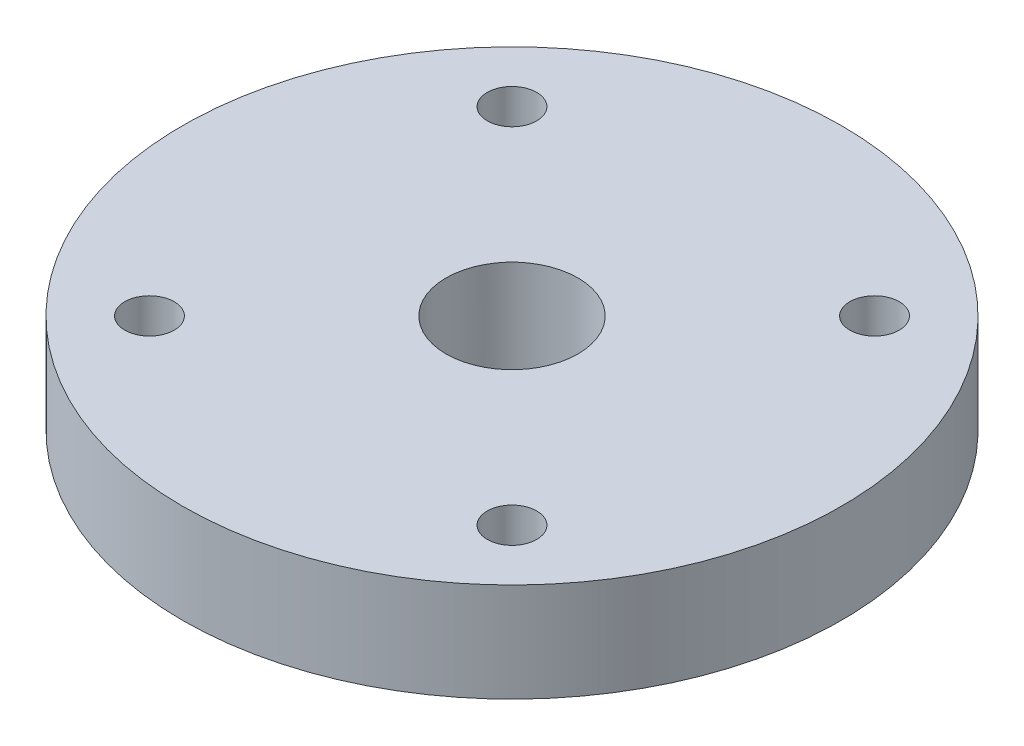
SolidWorks part; units mm, degrees
material "Acrylic (Medium-high impact)"
ref_plane "Front Plane" through (0, 0, 0) normal (0, 0, 1) x (1, 0, 0)
ref_plane "Top Plane" through (0, 0, 0) normal (0, 1, 0) x (1, 0, 0)
ref_plane "Right Plane" through (0, 0, 0) normal (1, 0, 0) x (0, 0, -1)
sketch "Sketch1" plane through (0, 0, 0) normal (0, 1, 0) x (1, 0, 0)
  circle A0 centre (0, 0) radius 20
  dimension "D1" = 40
extrude "Arm Distans Boss-Extrude1" add sketch "Sketch1" along normal blind 6
sketch "Sketch2" plane through (0, 6, 0) normal (0, 1, 0) x (1, 0, 0)
  line L0 (-11, 11) -> (0, 0) construction
  line L1 (11, 11) -> (-11, 11) construction
  line L2 (11, 11) -> (11, -11) construction
  line L3 (11, -11) -> (-11, -11) construction
  line L4 (-11, 11) -> (-11, -11) construction
  line L5 (0, 0) -> (-11, -11) construction
  line L6 (0, 0) -> (11, -11) construction
  line L7 (0, 0) -> (11, 11) construction
  circle A0 centre (11, 11) radius 1.5
  circle A1 centre (-11, 11) radius 1.5
  circle A2 centre (-11, -11) radius 1.5
  circle A3 centre (11, -11) radius 1.5
  dimension "D2" = 3
  dimension "D1" = 22
extrude "Mounting Holes Cut-Extrude1" cut sketch "Sketch2" against normal up to surface (6 mm away) up to face at (0, 0, 20)
sketch "Sketch3" plane through (0, 0, 0) normal (0, -1, 0) x (1, 0, 0)
  circle A0 centre (0, 0) radius 4
  dimension "D1" = 8
extrude "Cut-Extrude1" cut sketch "Sketch3" against normal up to surface (6 mm away) up to face at (11, 6, 12.5)
